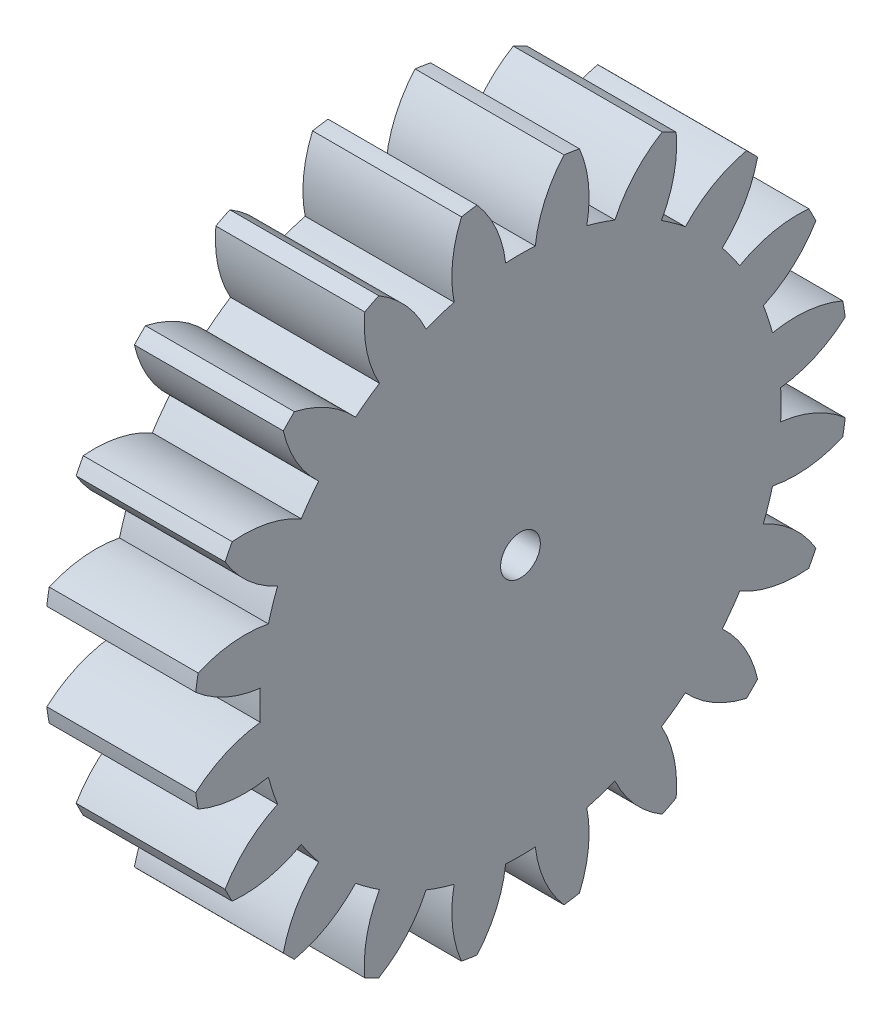
SolidWorks part; units mm, degrees
ref_plane "Plane1" through (0, 0, 0) normal (0, 0, 1) x (1, 0, 0)
ref_plane "Plane2" through (0, 0, 0) normal (0, 1, 0) x (1, 0, 0)
ref_plane "Plane3" through (0, 0, 0) normal (1, 0, 0) x (0, 0, -1)
other "Configuration Table"
sketch "HoldingSke" plane through (0, 0, 0) normal (0, 1, 0) x (1, 0, 0)
  line L0 (0, 0) -> (0.3132, -0.114)
  line L1 (-15, 0) -> (100, 0) construction
  line L2 (0, 0) -> (-2.1039, 2.3779)
  line L3 (0, 0) -> (-11.863, 4.5341)
  line L4 (0, 0) -> (8.1152, 2.9537)
  line L5 (0, 0) -> (-46.8476, -17.4728)
  line L6 (0, 0) -> (-12.4344, -8.3896)
  line L7 (-2.1039, 2.3779) -> (8.6586, 51.2059)
  line L8 (-76.2, 54.61) -> (-75.5, 54.61)
  line L9 (-71.009, 38.7566) -> (-53.1078, 45.2721)
  line L10 (-76.2, 71.12) -> (104.1128, 71.12)
  line L11 (0, 0) -> (-15, 0)
  line L12 (-76.2, 101.6) -> (-76.093, 101.6)
  line L13 (24.9733, 27.94) -> (52.9518, 28.4284)
  line L14 (24.9733, 27.94) -> (24.9743, 27.94)
  line L15 (24.9733, 27.94) -> (100.4006, 29.5858)
  line L16 (-63.627, -3) -> (-12.827, -3)
  circle A0 centre (0, 0) radius 2
  circle A1 centre (0, 0) radius 26.249
  circle A2 centre (0, 0) radius 37.5
  circle A3 centre (0, 0) radius 2
  dimension "Hub_dia" = 75
  dimension "Bore" = 4
  dimension "MBD" = 4
  dimension "Num_teeth" = 20
  dimension "Overall_len" = 50
  dimension "Show_teeth" = 20
  dimension "OAL" = 50.0001
  dimension "T_dim" = 0.7
  dimension "Ap" = 20
  dimension "H" = 19.05
  dimension "Pitch_radius" = 180.3128
  dimension "Addendum_fac" = 1
  dimension "Dedendum_fac" = 1.25
  dimension "Clearance_fac" = 0.25
  dimension "Dedendum_add" = 0.001
sketch "BasProSke" plane through (0, 0, 0) normal (0, 1, 0) x (1, 0, 0)
  line L0 (-10, 0) -> (60, 0) construction
  line L1 (0, 0) -> (0, 33)
  line L2 (0, 0) -> (15, 0)
  line L3 (15, 0) -> (15, 33)
  line L4 (15, 33) -> (0, 33)
revolve "Base-Revolve" add sketch "BasProSke" angle 360 about L0
sketch "TooCutSke" plane through (0, 0, 0) normal (1, 0, 0) x (0, 0, -1)
  line L1 (0, 0) -> (0, 107) construction
  line L2 (0, 0) -> (-2.5409, 29.8922) construction
  line L3 (0, 0) -> (-9.3616, 59.1066) construction
  line L4 (-2.5409, 29.8922) -> (-4.6808, 29.5533) construction
  arc A0 (1.4893, 26.2067) -> (-1.4893, 26.2067) centre (0, 0) ccw
  arc A1 (4.4016, 32.7308) -> (-4.4016, 32.7308) centre (0, 0) ccw
  circle A2 centre (0, 0) radius 30 construction
  circle A3 centre (0, 0) radius 28.1908 construction
  arc A4 (-1.4893, 26.2067) -> (-4.4016, 32.7308) centre (-13.4064, 24.799) ccw
  arc A5 (4.4016, 32.7308) -> (1.4893, 26.2067) centre (13.4064, 24.799) ccw
  dimension "Half_ang" = 9
extrude "ToothCut" cut sketch "TooCutSke" along normal through all
fillet "Breaks" [suppressed] radius 0.06
fillet "RootFillets" [suppressed] radius 0.751
pattern_circular "TeethCuts" count 20 every 18 about axis through (-10, 0, 0) along (1, 0, 0) of "ToothCut", "RootFillets", "Breaks"
sketch "HubNeaOneSke" plane through (0, 0, 0) normal (-1, 0, 0) x (0, 0, 1)
  circle A0 centre (0, 0) radius 26.249
extrude "HubNearOne" [suppressed] add sketch "HubNeaOneSke" along normal blind 35.0001
sketch "HubNeaBotSke" plane through (0, 0, 0) normal (-1, 0, 0) x (0, 0, 1)
  circle A0 centre (0, 0) radius 26.249
extrude "HubNearBoth" [suppressed] add sketch "HubNeaBotSke" along normal blind 17.5
ref_plane "FarPln" through (15, 0, 0) normal (1, 0, 0) x (0, 0, -1)
sketch "HubFarSke" plane through (15, 0, 0) normal (1, 0, 0) x (0, 0, -1)
  circle A0 centre (0, 0) radius 26.249
extrude "HubFar" [suppressed] add sketch "HubFarSke" along normal blind 17.5
sketch "BorSke" plane through (0, 0, 0) normal (1, 0, 0) x (0, 0, -1)
  circle A0 centre (0, 0) radius 2
  dimension "Diameter" = 4
extrude "Bore" cut sketch "BorSke" along normal mid plane 100.0001
sketch "KeySke" plane through (0, 0, 0) normal (1, 0, 0) x (0, 0, -1)
  line L0 (-0.8, 0) -> (-0.8, 2.7)
  line L1 (-0.8, 2.7) -> (0.8, 2.7)
  line L2 (0.8, 2.7) -> (0.8, 0)
  line L3 (0, 0) -> (0, 34) construction
  line L4 (-0.8, 0) -> (0.8, 0)
  dimension "Offset" = 2.7
  dimension "Width" = 1.6
extrude "Keyway" [suppressed] cut sketch "KeySke" along normal mid plane 100.0001
pattern_circular "Keyway2" [suppressed] count 2 every 90 about axis through (-10, 0, 0) along (1, 0, 0)
equation "' \"Module@HoldingSke\" = 6.35"
equation "' \"Num_teeth@HoldingSke\" = 12"
equation "' \"Ap@HoldingSke\" =  20"
equation "' \"Ap@HoldingSke\" = 20"
equation "' \"Width@HoldingSke\" = 0.5 * 25.4"
equation "' \"Hub_dia@HoldingSke\"= 1 * 25.4"
equation "' \"Hub_dia@HoldingSke\" = 1 * 25.4"
equation "' \"Overall_len@HoldingSke\" = 1.0 * 25.4"
equation "' \"Bore@HoldingSke\" = 0.75 * 25.4"
equation "' \"T_dim@HoldingSke\" = 0.1 * 25.4"
equation "' \"Width@KeySke\" = 0.25 * 25.4"
equation "' \"Show_teeth@HoldingSke\" = 13"
equation "' \"Backlash@HoldingSke\" = 0.009 * 25.4"
equation "' \"Addendum_fac@HoldingSke\" = 1.0"
equation "' \"Dedendum_fac@HoldingSke\" = 1.25"
equation "' \"Dedendum_add@HoldingSke\" = 0.00005 * 25.4"
equation "' \"Clearance_fac@HoldingSke\" = 0.25"
equation "\"Pitch@HoldingSke\" = 1 / \"Module@HoldingSke\""
equation "\"Overcut_dia@TooCutSke\" = (\"Num_teeth@HoldingSke\" + 2 * \"Addendum_fac@HoldingSke\") / \"Pitch@HoldingSke\" + 0.002 * 25.4"
equation "\"Pitch_dia@TooCutSke\" = \"Num_teeth@HoldingSke\" / \"Pitch@HoldingSke\""
equation "\"Base_dia@TooCutSke\" = \"Num_teeth@HoldingSke\" / \"Pitch@HoldingSke\" * cos((\"Ap@HoldingSke\"  * 3.14159265 / 180))"
equation "\"Root_dia@TooCutSke\" = (\"Num_teeth@HoldingSke\" + 2) / \"Pitch@HoldingSke\" - 2 * (\"Addendum_fac@HoldingSke\" + \"Dedendum_fac@HoldingSke\") / \"Pitch@HoldingSke\" - \"Dedendum_add@HoldingSke\" * 2"
equation "\"Half_ang@TooCutSke\" = 180 / \"Num_teeth@HoldingSke\""
equation "\"Half_CT@TooCutSke\" = \"Num_teeth@HoldingSke\" / \"Pitch@HoldingSke\" * sin((3.14159265 / 2 / \"Num_teeth@HoldingSke\")) / 2 - 7 * \"Backlash@HoldingSke\" / 4"
equation "\"Flank_rad@TooCutSke\" = \"Num_teeth@HoldingSke\" / \"Pitch@HoldingSke\" / 5"
equation "\"Radius@RootFillets\" = \"Clearance_fac@HoldingSke\" / \"Pitch@HoldingSke\" + \"Dedendum_add@HoldingSke\""
equation "\"Break_rad@Breaks\" = 0.02 / \"Pitch@HoldingSke\""
equation "\"Thickness@HoldingSke\" = \"Width@HoldingSke\""
equation "\"OAL@HoldingSke\" = \"Thickness@HoldingSke\""
equation "\"MHD@HoldingSke\" = (\"Num_teeth@HoldingSke\" + 2) / \"Pitch@HoldingSke\" - 2 * (\"Addendum_fac@HoldingSke\" + \"Dedendum_fac@HoldingSke\")  / \"Pitch@HoldingSke\" - \"Dedendum_add@HoldingSke\" * 2"
equation "\"MBD@HoldingSke\" = (\"Num_teeth@HoldingSke\" + 2) / \"Pitch@HoldingSke\" - 2 * (\"Addendum_fac@HoldingSke\" + \"Dedendum_fac@HoldingSke\")  / \"Pitch@HoldingSke\" - \"Dedendum_add@HoldingSke\" * 2 - 0.002 * 25.4"
equation "\"MHD@HoldingSke\" = ((sgn( \"MHD@HoldingSke\" - \"Hub_dia@HoldingSke\" )-1)*( \"MHD@HoldingSke\" - \"Hub_dia@HoldingSke\" ))/-2+ \"Hub_dia@HoldingSke\""
equation "\"MBD@HoldingSke\" = ((sgn( \"MBD@HoldingSke\" - \"Bore@HoldingSke\" )-1)*( \"MBD@HoldingSke\" - \"Bore@HoldingSke\" ))/-2+ \"Bore@HoldingSke\""
equation "\"OAL@HoldingSke\" = ((sgn( \"OAL@HoldingSke\" - \"Overall_len@HoldingSke\" )+1)*( \"OAL@HoldingSke\" - \"Overall_len@HoldingSke\" ))/2 + \"Overall_len@HoldingSke\" + 0.000002 * 25.4"
equation "\"Num_teeth@TeethCuts\" = int( \"Show_teeth@HoldingSke\" ) + 1"
equation "\"Num_teeth@TeethCuts\" = ((sgn( \"Num_teeth@TeethCuts\" - \"Num_teeth@HoldingSke\" )-1)*( \"Num_teeth@TeethCuts\" - \"Num_teeth@HoldingSke\" ))/-2+ \"Num_teeth@HoldingSke\""
equation "\"Num_teeth@TeethCuts\" = ((sgn( \"Num_teeth@TeethCuts\" - 2.0)+1)*( \"Num_teeth@TeethCuts\" - 2.0))/2 +2.0"
equation "\"Angle@TeethCuts\" = 360.0 / \"Num_teeth@HoldingSke\""
equation "\"Diameter@BasProSke\" = (\"Num_teeth@HoldingSke\" + 2 * \"Addendum_fac@HoldingSke\") / \"Pitch@HoldingSke\""
equation "\"Thickness@BasProSke\"  = \"Thickness@HoldingSke\""
equation "' \"Fillet_rad@BasProSke\" =  \"Thickness@HoldingSke\" * 0.05"
equation "' \"Fillet_rad@BasProSke\" = \"Thickness@HoldingSke\" * 0.05"
equation "\"MHD@HoldingSke\" = ((sgn( \"MHD@HoldingSke\" - \"Root_dia@TooCutSke\" )-1)*( \"MHD@HoldingSke\" - \"Root_dia@TooCutSke\" ))/-2+ \"Root_dia@TooCutSke\""
equation "\"Diameter@HubNeaOneSke\" = \"MHD@HoldingSke\""
equation "\"Length@HubNearOne\" = \"OAL@HoldingSke\" - \"Thickness@BasProSke\""
equation "\"Diameter@HubNeaBotSke\" = \"MHD@HoldingSke\""
equation "\"Length@HubNearBoth\" = ( \"OAL@HoldingSke\" - \"Thickness@BasProSke\" ) / 2.0"
equation "\"Thickness@FarPln\" = \"Thickness@BasProSke\""
equation "\"Diameter@HubFarSke\" = \"MHD@HoldingSke\""
equation "\"Length@HubFar\" = ( \"OAL@HoldingSke\" - \"Thickness@BasProSke\" ) / 2.0"
equation "\"Diameter@BorSke\" = \"MBD@HoldingSke\""
equation "\"D1@Bore\" = \"OAL@HoldingSke\" * 2.0"
equation "\"D1@Keyway\" = \"OAL@HoldingSke\" * 2.0"
equation "\"Offset@KeySke\" = \"T_dim@HoldingSke\" + \"MBD@HoldingSke\" / 2.0"
